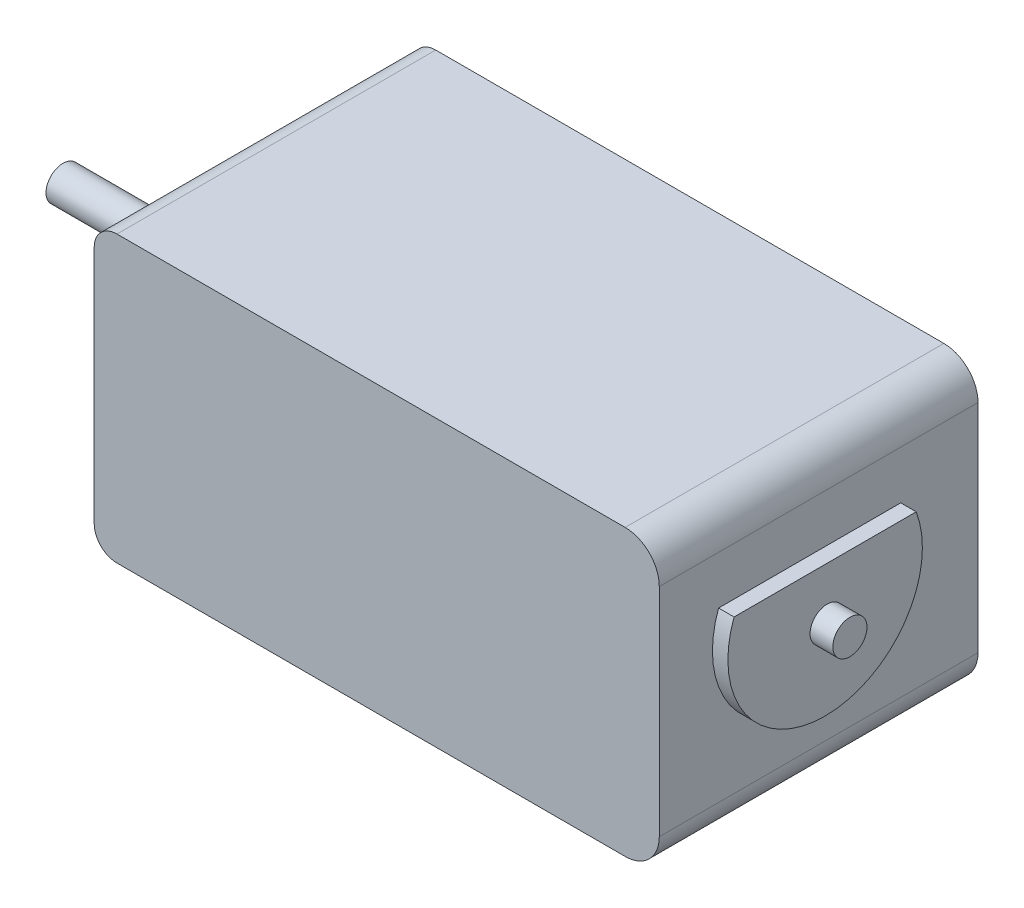
SolidWorks part; units mm, degrees
ref_plane "Front Plane" through (0, 0, 0) normal (0, 0, 1) x (1, 0, 0)
ref_plane "Top Plane" through (0, 0, 0) normal (0, 1, 0) x (1, 0, 0)
ref_plane "Right Plane" through (0, 0, 0) normal (1, 0, 0) x (0, 0, -1)
sketch "Sketch1" plane through (0, 0, 0) normal (0, 0, 1) x (1, 0, 0)
  line L1 (1, 0) -> (23.3209, 0)
  line L2 (0, -1) -> (0, -11.517)
  line L3 (1, -12.517) -> (23.3209, -12.517)
  line L4 (24.8209, -1.5) -> (24.8209, -11.017)
  arc A2 (24.8209, -1.5) -> (23.3209, 0) centre (23.3209, -1.5) ccw
  arc A3 (23.3209, -12.517) -> (24.8209, -11.017) centre (23.3209, -11.017) ccw
  arc A4 (0, -1) -> (1, 0) centre (1, -1) cw
  arc A5 (1, -12.517) -> (0, -11.517) centre (1, -11.517) cw
  point P4 (10, -6.5)
  point P9 (0, 0)
  dimension "D2" = 1
  dimension "D4" = 1.5
  dimension "D5" = 1.5
  dimension "D1" = 1
extrude "Boss-Extrude1" add sketch "Sketch1" along normal blind 14
sketch "Sketch2" plane through (0, 0, 0) normal (1, 0, 0) x (0, 0, -1)
  circle A0 centre (-7.3678, -5.8723) radius 2.25
  circle A1 centre (-7.3678, -5.8723) radius 2.5
  circle A2 centre (-7.3678, -5.8723) radius 0.75
  dimension "D1" = 5
  dimension "D2" = 4.5
  dimension "D3" = 1.5
extrude "Boss-Extrude3" add sketch "Sketch2" against normal blind 1.5 contours A0 | A1
sketch "Sketch3" plane through (0, 0, 0) normal (-1, 0, 0) x (0, 0, 1)
  circle A0 centre (7.3678, -5.8723) radius 0.75
  dimension "D1" = 1.5
extrude "Boss-Extrude4" add sketch "Sketch3" along normal blind 8
sketch "Sketch7" plane through (0, 0, 0) normal (1, 0, 0) x (0, 0, -1)
  line L0 (-11.3944, -3.6202) -> (-3.3934, -3.6202)
  arc A0 (-11.3944, -3.6202) -> (-3.3934, -3.6202) centre (-7.3939, -5.1182) ccw
  circle A1 centre (-7.3939, -5.1182) radius 0.412
  point P6 (-7.3939, -3.6202)
extrude "Boss-Extrude5" add sketch "Sketch7" along direction (-1, 0, 0) on the side of the normal blind 25.5 contours A0 L0
sketch "Sketch8" plane through (25.5, 0, 0) normal (1, 0, 0) x (0, 0, -1)
  circle A0 centre (-7.3483, -5.9046) radius 0.75
extrude "Boss-Extrude7" add sketch "Sketch8" against normal blind 1
sketch "Sketch9" plane through (25.5, 0, 0) normal (1, 0, 0) x (0, 0, -1)
  circle A0 centre (-7.3059, -5.9261) radius 0.75
extrude "Boss-Extrude8" add sketch "Sketch9" along normal blind 1
